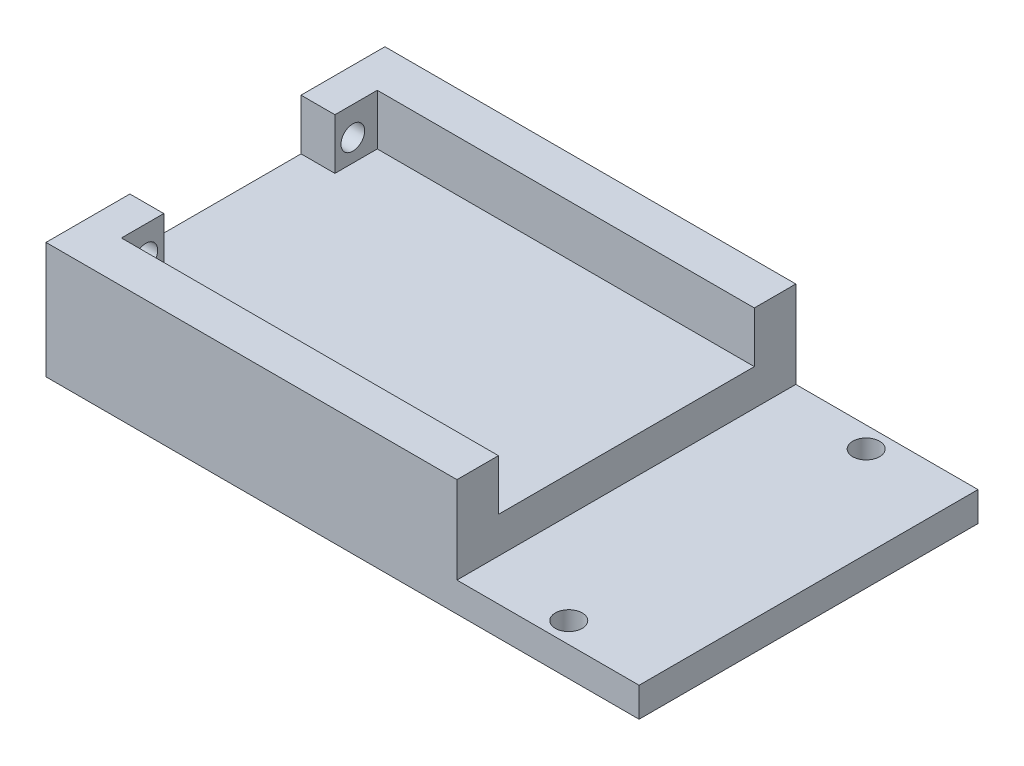
SolidWorks part; units mm, degrees
ref_plane "Front Plane" through (0, 0, 0) normal (0, 0, 1) x (1, 0, 0)
ref_plane "Top Plane" through (0, 0, 0) normal (0, 1, 0) x (1, 0, 0)
ref_plane "Right Plane" through (0, 0, 0) normal (1, 0, 0) x (0, 0, -1)
sketch "Sketch1" plane through (0, 0, 0) normal (0, 0, 1) x (1, 0, 0)
  line L0 (140, 0) -> (0, 0)
  line L1 (0, 0) -> (0, 15.49)
  line L2 (0, 15.49) -> (97, 15.49)
  line L3 (97, 15.49) -> (97, 6.96)
  line L4 (97, 6.96) -> (140, 6.96)
  line L5 (140, 6.96) -> (140, 0)
  dimension "D1" = 97
  dimension "D2" = 6.96
  dimension "D3" = 15.49
  dimension "D4" = 140
extrude "Boss-Extrude1" add sketch "Sketch1" along normal blind 80
sketch "Sketch2" plane through (0, 15.49, 0) normal (0, 1, 0) x (1, 0, 0)
  line L0 (0, 0) -> (0, -9.8)
  line L1 (0, -80) -> (0, 0) construction
  line L2 (8, -9.8) -> (97, -9.8)
  line L3 (97, -80) -> (97, 0) construction
  line L4 (97, -9.8) -> (97, 0)
  line L5 (97, 0) -> (0, 0)
  line L6 (0, -80) -> (97, -80)
  line L7 (97, -80) -> (97, -70.2)
  line L8 (97, -70.2) -> (8, -70.2)
  line L9 (0, -70.2) -> (0, -80)
  line L10 (0, -60.2) -> (8, -60.2)
  line L11 (8, -60.2) -> (8, -70.2)
  line L13 (0, -9.8) -> (0, -19.8)
  line L14 (0, -19.8) -> (8, -19.8)
  line L15 (8, -19.8) -> (8, -9.8)
  line M3 (97, 0) -> (0, 0)
  line M4 (0, 0) -> (0, -80)
  line M5 (0, -80) -> (97, -80)
  line M6 (97, -80) -> (97, 0)
  dimension "D1" = 9.8
  dimension "D2" = 9.8
  dimension "D3" = 10
  dimension "D4" = 8
  dimension "D5" = 10
  dimension "D6" = 8
  dimension "D7" = 9.8
  dimension "D8" = 9.8
extrude "Boss-Extrude2" add sketch "Sketch2" along normal blind 12 contours L14 L15 L2 M6 M3 M4 | L11 L10 L8 M4 M5 M6
sketch "Sketch3" plane through (0, 0, 0) normal (-1, 0, 0) x (0, 0, 1)
  line L0 (19.8, 20.72) -> (15.57, 20.72) construction
  line L2 (15.57, 20.72) -> (15.57, 27.49) construction
  line L3 (0, 27.49) -> (19.8, 27.49) construction
  line L4 (60.2, 20.72) -> (64.43, 20.72) construction
  line L6 (64.43, 20.72) -> (64.43, 27.49) construction
  line L7 (60.2, 27.49) -> (80, 27.49) construction
  line L8 (19.8, 27.49) -> (19.8, 15.49) construction
  line L9 (60.2, 27.49) -> (60.2, 15.49) construction
  circle A0 centre (15.57, 20.72) radius 2.795
  circle A1 centre (64.43, 20.72) radius 2.795
extrude "Cut-Extrude1" cut sketch "Sketch3" against normal blind 60
sketch "Sketch4" plane through (0, 6.96, 0) normal (0, 1, 0) x (1, 0, 0)
  line L0 (97, -4.9) -> (140, -4.9) construction
  line L1 (97, -9.8) -> (97, 0) construction
  line L2 (140, -80) -> (140, 0) construction
  line L3 (97, -75.1) -> (140, -75.1) construction
  line L4 (97, -80) -> (97, -70.2) construction
  circle A0 centre (118.5, -4.9) radius 3.175
  circle A1 centre (118.5, -75.1) radius 3.175
  dimension "D1" = 6.35
  dimension "D2" = 6.35
extrude "Cut-Extrude2" cut sketch "Sketch4" against normal blind 10
